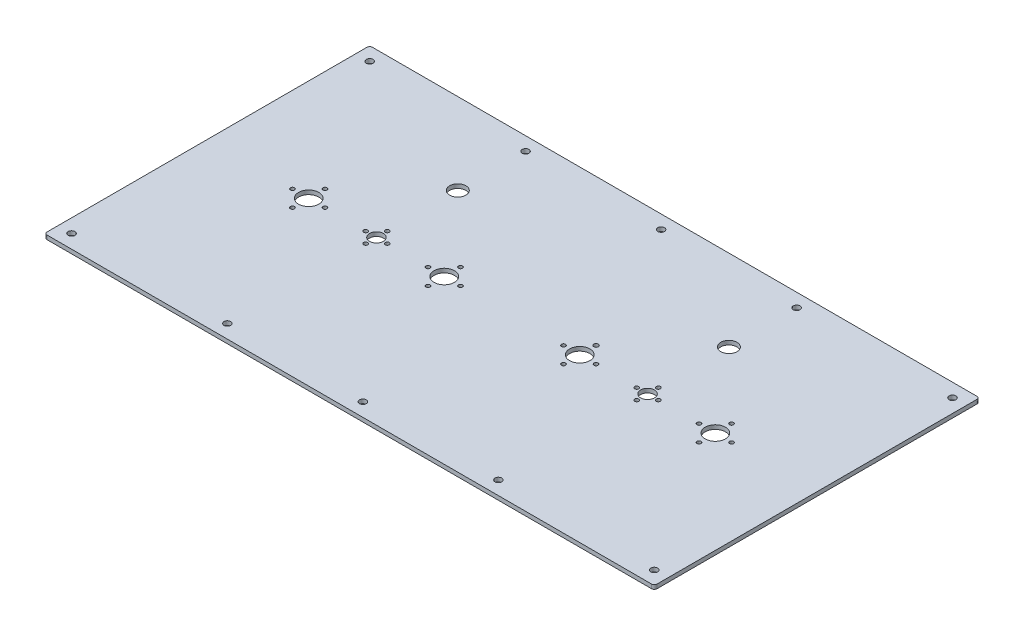
SolidWorks part; units mm, degrees
ref_plane "前视基准面" through (0, 0, 0) normal (0, 0, 1) x (1, 0, 0)
ref_plane "上视基准面" through (0, 0, 0) normal (0, 1, 0) x (1, 0, 0)
ref_plane "右视基准面" through (0, 0, 0) normal (1, 0, 0) x (0, 0, -1)
sketch "草图1" plane through (0, 0, 0) normal (0, 1, 0) x (1, 0, 0)
  line L0 (300, 100) -> (300, 160)
  line L1 (-23, 220) -> (423, 220)
  line L2 (-25, 218) -> (-25, -18)
  line L3 (-23, -20) -> (423, -20)
  line L4 (425, 218) -> (425, -18)
  line L6 (415, -10) -> (322.8759, -10) construction
  line L7 (250, 100) -> (150, 100) construction
  line L8 (415, 210) -> (322.8759, 210) construction
  line L15 (100, 100) -> (100, 160)
  line L33 (100, 100) -> (150, 100)
  circle A0 centre (100, 100) radius 5.1
  circle A1 centre (150, 112) radius 1.5
  circle A2 centre (100, 92) radius 1.5
  circle A3 centre (108, 100) radius 1.5
  circle A4 centre (92, 100) radius 1.5
  circle A5 centre (100, 108) radius 1.5
  circle A6 centre (50, 100) radius 7.5
  circle A7 centre (50, 112) radius 1.5
  circle A8 centre (62, 100) radius 1.5
  circle A9 centre (50, 88) radius 1.5
  circle A10 centre (38, 100) radius 1.5
  circle A11 centre (162, 100) radius 1.5
  circle A12 centre (138, 100) radius 1.5
  circle A13 centre (150, 88) radius 1.5
  circle A14 centre (150, 100) radius 7.5
  circle A15 centre (100, 160) radius 6
  circle A16 centre (300, 100) radius 5.1
  circle A17 centre (350, 112) radius 1.5
  circle A18 centre (300, 108) radius 1.5
  circle A19 centre (308, 100) radius 1.5
  circle A20 centre (300, 92) radius 1.5
  circle A21 centre (292, 100) radius 1.5
  circle A22 centre (250, 100) radius 7.5
  circle A23 centre (250, 112) radius 1.7
  circle A24 centre (262, 100) radius 1.5
  circle A25 centre (250, 88) radius 1.5
  circle A26 centre (238, 100) radius 1.5
  circle A27 centre (362, 100) radius 1.5
  circle A28 centre (338, 100) radius 1.5
  circle A29 centre (350, 88) radius 1.5
  circle A30 centre (350, 100) radius 7.5
  circle A31 centre (300, 160) radius 6
  arc A32 (425, 218) -> (423, 220) centre (423, 218) ccw
  arc A33 (423, -20) -> (425, -18) centre (423, -18) ccw
  arc A34 (-23, -20) -> (-25, -18) centre (-23, -18) cw
  arc A35 (-23, 220) -> (-25, 218) centre (-23, 218) ccw
  circle A36 centre (415, -10) radius 2.5
  circle A37 centre (100, -10) radius 2.5
  circle A38 centre (300, -10) radius 2.5
  circle A39 centre (-15, -10) radius 2.5
  circle A40 centre (200, -10) radius 2.5
  circle A41 centre (200, 210) radius 2.5
  circle A42 centre (-15, 210) radius 2.5
  circle A43 centre (300, 210) radius 2.5
  circle A44 centre (100, 210) radius 2.5
  circle A45 centre (415, 210) radius 2.5
  point P19 (300, 100)
  point P38 (300, 100)
  point P46 (100, 100)
  point P52 (350, 100)
  point P66 (50, 100)
  point P74 (150, 100)
  point P81 (-25, -20)
  point P84 (-25, 220)
  point P111 (100, 100)
  dimension "D2" = 12
  dimension "D3" = 50
  dimension "D4" = 12
  dimension "D7" = 450
  dimension "D15" = 2
  dimension "D16" = 5
  dimension "D19" = 125
  dimension "D20" = 10
  dimension "D21" = 125
  dimension "D22" = 225
  dimension "D23" = 50
  dimension "D24" = 3
  dimension "D25" = 3
  dimension "D26" = 3
  dimension "D27" = 3
  dimension "D28" = 3
  dimension "D29" = 3
  dimension "D30" = 3
  dimension "D31" = 3
  dimension "D32" = 3
  dimension "D1" = 240
  dimension "D8" = 120
  dimension "D9" = 125
  dimension "D10" = 50
  dimension "D11" = 12
  dimension "D12" = 12
  dimension "D13" = 120
  dimension "D14" = 125
  dimension "D17" = 10
  dimension "D18" = 10
  dimension "D33" = 4
  dimension "D5" = 4
  dimension "D6" = 4
extrude "凸台-拉伸1" add sketch "草图1" along normal blind 3
